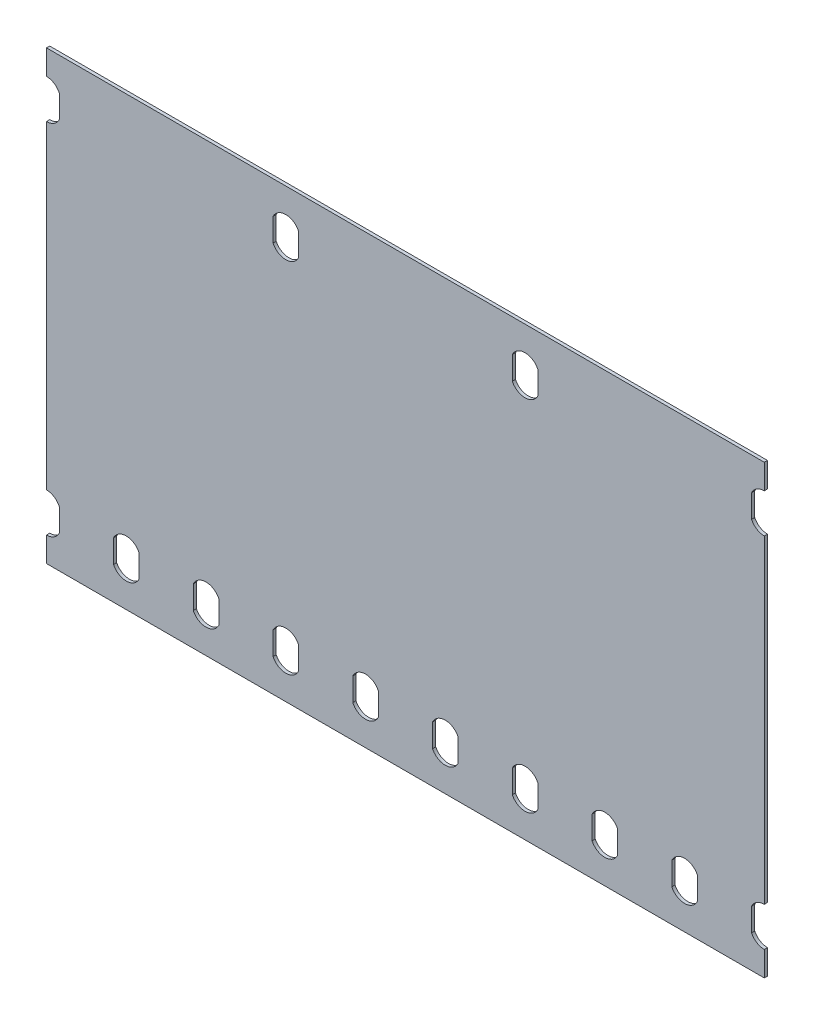
SolidWorks part; units mm, degrees
ref_plane "Front Plane" through (0, 0, 0) normal (0, 0, 1) x (1, 0, 0)
ref_plane "Top Plane" through (0, 0, 0) normal (0, 1, 0) x (1, 0, 0)
ref_plane "Right Plane" through (0, 0, 0) normal (1, 0, 0) x (0, 0, -1)
sketch "Sketch1" plane through (0, 0, 0) normal (0, 0, 1) x (1, 0, 0)
  line L0 (15, 24) -> (0, 24)
  line L1 (0, 0) -> (45, 0)
  line L2 (0, 4) -> (45, 4)
  line L3 (0, 28) -> (45, 28)
  line L4 (15, 24) -> (30, 24)
  line L5 (15.8, 25.95) -> (15.8, 24.5)
  line L6 (15, 24) -> (15, 4)
  line L7 (30, 24) -> (30, 4)
  line L8 (30.8, 24.5) -> (30.8, 25.95)
  line L9 (29.2, 25.95) -> (29.2, 24.5)
  line L10 (30, 24) -> (45, 24)
  line L11 (0, 0) -> (0, 1.55)
  line L12 (44.2, 24.5) -> (44.2, 25.95)
  line L13 (0, 28) -> (0, 26.45)
  line L14 (45.8, 25.95) -> (45.8, 24.5)
  line L15 (-0.8, 25.95) -> (-0.8, 24.5)
  line L16 (0.8, 24.5) -> (0.8, 25.95)
  line L17 (14.2, 3.5) -> (14.2, 2.05)
  line L18 (0, 24) -> (0, 4)
  line L19 (15.8, 2.05) -> (15.8, 3.5)
  line L20 (45, 28) -> (45, 26.45)
  line L21 (29.2, 2.05) -> (29.2, 3.5)
  line L22 (14.2, 24.5) -> (14.2, 25.95)
  line L23 (30.8, 3.5) -> (30.8, 2.05)
  line L24 (45, 24) -> (45, 4)
  line L25 (45, 0) -> (45, 1.55)
  line L26 (9.2, 2.05) -> (9.2, 3.5)
  line L27 (10.8, 3.5) -> (10.8, 2.05)
  line L28 (4.2, 3.5) -> (4.2, 2.05)
  line L29 (5.8, 2.05) -> (5.8, 3.5)
  line L30 (-0.8, 2.05) -> (-0.8, 3.5)
  line L31 (0.8, 3.5) -> (0.8, 2.05)
  line L32 (44.2, 3.5) -> (44.2, 2.05)
  line L33 (29.2, 3.5) -> (29.2, 2.05)
  line L34 (30.8, 2.05) -> (30.8, 3.5)
  line L35 (24.2, 2.05) -> (24.2, 3.5)
  line L36 (25.8, 3.5) -> (25.8, 2.05)
  line L37 (19.2, 3.5) -> (19.2, 2.05)
  line L38 (20.8, 2.05) -> (20.8, 3.5)
  line L39 (45.8, 2.05) -> (45.8, 3.5)
  line L40 (39.2, 2.05) -> (39.2, 3.5)
  line L41 (40.8, 3.5) -> (40.8, 2.05)
  line L42 (34.2, 3.5) -> (34.2, 2.05)
  line L43 (35.8, 2.05) -> (35.8, 3.5)
  arc A0 (14.2, 25.95) -> (15.8, 25.95) centre (15, 25.56) cw
  arc A1 (14.2, 24.5) -> (15.8, 24.5) centre (15, 24.89) ccw
  arc A2 (30.8, 24.5) -> (29.2, 24.5) centre (30, 24.89) cw
  arc A3 (30.8, 25.95) -> (29.2, 25.95) centre (30, 25.56) ccw
  arc A4 (14.2, 3.5) -> (15.8, 3.5) centre (15, 3.11) cw
  arc A5 (14.2, 2.05) -> (15.8, 2.05) centre (15, 2.44) ccw
  arc A6 (30.8, 3.5) -> (29.2, 3.5) centre (30, 3.11) ccw
  arc A7 (30.8, 2.05) -> (29.2, 2.05) centre (30, 2.44) cw
  arc A8 (10.8, 2.05) -> (9.2, 2.05) centre (10, 2.44) cw
  arc A9 (10.8, 3.5) -> (9.2, 3.5) centre (10, 3.11) ccw
  arc A10 (4.2, 3.5) -> (5.8, 3.5) centre (5, 3.11) cw
  arc A11 (4.2, 2.05) -> (5.8, 2.05) centre (5, 2.44) ccw
  arc A12 (0.8, 2.05) -> (-0.8, 2.05) centre (0, 2.44) cw
  arc A13 (0.8, 3.5) -> (-0.8, 3.5) centre (0, 3.11) ccw
  arc A14 (29.2, 3.5) -> (30.8, 3.5) centre (30, 3.11) cw
  arc A15 (29.2, 2.05) -> (30.8, 2.05) centre (30, 2.44) ccw
  arc A16 (25.8, 2.05) -> (24.2, 2.05) centre (25, 2.44) cw
  arc A17 (25.8, 3.5) -> (24.2, 3.5) centre (25, 3.11) ccw
  arc A18 (19.2, 3.5) -> (20.8, 3.5) centre (20, 3.11) cw
  arc A19 (19.2, 2.05) -> (20.8, 2.05) centre (20, 2.44) ccw
  arc A20 (44.2, 3.5) -> (45.8, 3.5) centre (45, 3.11) cw
  arc A21 (44.2, 2.05) -> (45.8, 2.05) centre (45, 2.44) ccw
  arc A22 (40.8, 2.05) -> (39.2, 2.05) centre (40, 2.44) cw
  arc A23 (40.8, 3.5) -> (39.2, 3.5) centre (40, 3.11) ccw
  arc A24 (34.2, 3.5) -> (35.8, 3.5) centre (35, 3.11) cw
  arc A25 (34.2, 2.05) -> (35.8, 2.05) centre (35, 2.44) ccw
  arc A26 (44.2, 25.95) -> (45.8, 25.95) centre (45, 25.56) cw
  arc A27 (44.2, 24.5) -> (45.8, 24.5) centre (45, 24.89) ccw
  arc A28 (0.8, 24.5) -> (-0.8, 24.5) centre (0, 24.89) cw
  arc A29 (0.8, 25.95) -> (-0.8, 25.95) centre (0, 25.56) ccw
extrude "Boss-Extrude1" add sketch "Sketch1" along normal blind 0.2 contours L0 L18 L2 L6 | L24 L10 L7 L2 | A29 L16 A28 L0 A1 L22 A0 L5 L4 A2 L9 A3 L8 L10 A27 L12 A26 L20 L3 L13 | A25 L42 A24 L2 A6 L23 A7 L21 A17 L36 A16 L35 A18 L38 A19 L37 A4 L19 A5 L17 A9 L27 A8 L26 A10 L29 A11 L28 A13 L31 A12 L11 L1 L25 A21 L32 A20 A23 | L7 L4 L6 L2
